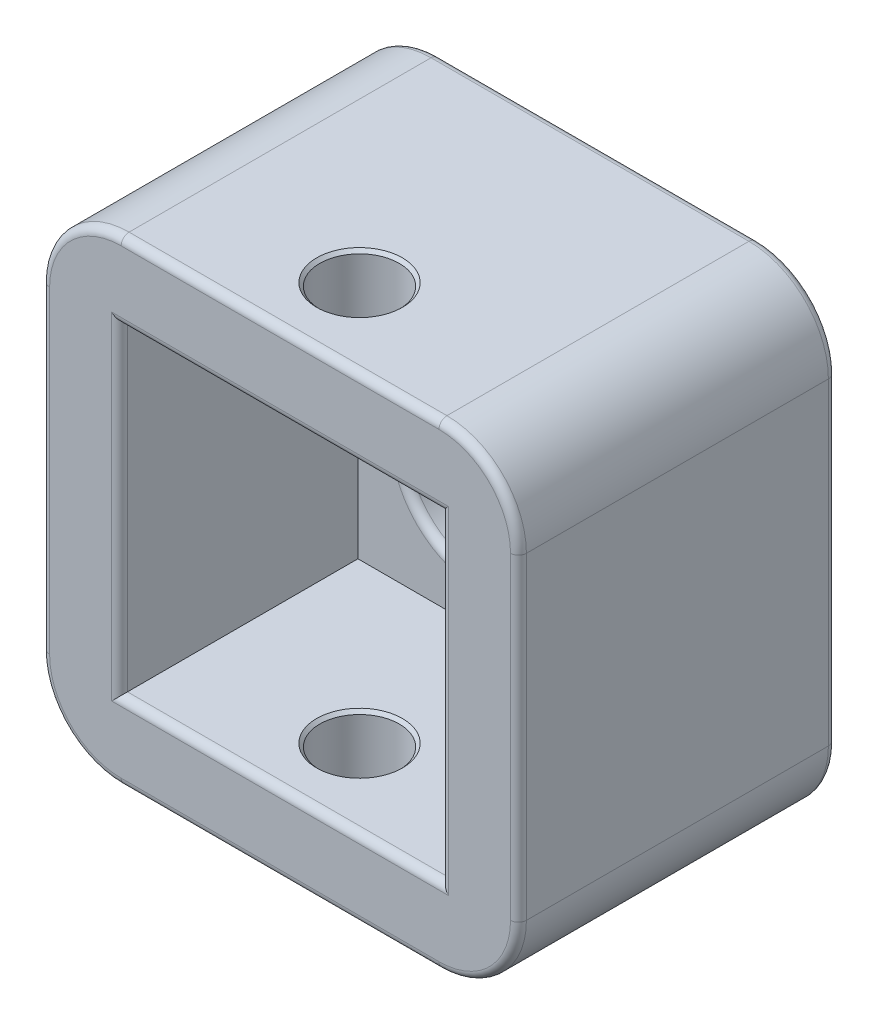
SolidWorks part; units mm, degrees
ref_plane "Front Plane" through (0, 0, 0) normal (0, 0, 1) x (1, 0, 0)
ref_plane "Top Plane" through (0, 0, 0) normal (0, 1, 0) x (1, 0, 0)
ref_plane "Right Plane" through (0, 0, 0) normal (1, 0, 0) x (0, 0, -1)
sketch "Sketch1" plane through (0, 0, 0) normal (0, 0, 1) x (1, 0, 0)
  line L1 (-15, -15) -> (15, -15)
  line L2 (-15, -15) -> (-15, 15)
  line L3 (-15, 15) -> (15, 15)
  line L4 (15, -15) -> (15, 15)
  line L5 (-15, -15) -> (15, 15) construction
  line L6 (-15, 15) -> (15, -15) construction
  point P0 (0, 0)
  dimension "D1" = 30
  dimension "D2" = 30
extrude "Boss-Extrude1" add sketch "Sketch1" along normal blind 20
sketch "Sketch2" plane through (0, 0, 20) normal (0, 0, 1) x (1, 0, 0)
  line L1 (-10.1, -10.1) -> (10.1, -10.1)
  line L2 (-10.1, -10.1) -> (-10.1, 10.1)
  line L3 (-10.1, 10.1) -> (10.1, 10.1)
  line L4 (10.1, -10.1) -> (10.1, 10.1)
  line L5 (-10.1, -10.1) -> (10.1, 10.1) construction
  line L6 (-10.1, 10.1) -> (10.1, -10.1) construction
  point P0 (0, 0)
  dimension "D1" = 20.2
  dimension "D2" = 20.2
extrude "Cut-Extrude1" cut sketch "Sketch2" against normal offset from surface (15 mm away) 5 up to face at (0, 0, 0)
sketch "Sketch3" plane through (0, -15, 0) normal (0, -1, 0) x (1, 0, 0)
  line L0 (-15, 20) -> (15, 20) construction
  circle A0 centre (0, 15) radius 2.5
  point P4 (0, 0)
  dimension "D1" = 5
  dimension "D2" = 5
extrude "Cut-Extrude2" cut sketch "Sketch3" against normal through all
sketch "Sketch4" plane through (0, 0, 5) normal (0, 0, 1) x (1, 0, 0)
  line L1 (-7.5, -7.5) -> (7.5, -7.5)
  line L2 (-7.5, -7.5) -> (-7.5, 7.5)
  line L3 (-7.5, 7.5) -> (7.5, 7.5)
  line L4 (7.5, -7.5) -> (7.5, 7.5)
  line L5 (-7.5, -7.5) -> (7.5, 7.5) construction
  line L6 (-7.5, 7.5) -> (7.5, -7.5) construction
  point P0 (0, 0)
  dimension "D1" = 15
  dimension "D2" = 15
extrude "Cut-Extrude3" cut sketch "Sketch4" against normal through all
fillet "Fillet2" radius 5 8 edges at (15, 15, 10) (-15, 15, 10) (-15, -15, 10) (15, -15, 10) (-7.5, -7.5, 2.5) (7.5, -7.5, 2.5) (7.5, 7.5, 2.5) (-7.5, 7.5, 2.5)
fillet "Fillet1" radius 0.5 36 edges at (0, 15, 0) (-15, 0, 0) (0, -15, 0) (15, 0, 0) (0, -15, 20) (-15, 0, 20) (0, 15, 20) (15, 0, 20) (0, -10.1, 20) (10.1, 0, 20) (0, 10.1, 20) (-10.1, 0, 20) (0, -7.5, 0) (-7.5, 0, 0) (0, 7.5, 0) (7.5, 0, 0) (0, -7.5, 5) (7.5, 0, 5) (0, 7.5, 5) (-7.5, 0, 5) (-6.0355, 6.0355, 5) (6.0355, 6.0355, 5) (6.0355, -6.0355, 5) (-6.0355, -6.0355, 5) (-13.5355, 13.5355, 0) (-13.5355, -13.5355, 0) (13.5355, -13.5355, 0) (13.5355, 13.5355, 0) (-6.0355, -6.0355, 0) (-6.0355, 6.0355, 0) (6.0355, 6.0355, 0) (6.0355, -6.0355, 0) (13.5355, -13.5355, 20) (-13.5355, -13.5355, 20) (-13.5355, 13.5355, 20) (13.5355, 13.5355, 20)
chamfer "Chamfer1" distance 0.2 angle 45 4 edges at (0, 10.1, 17.5) (0, 15, 12.5) (0, -10.1, 12.5) (0, -15, 12.5)
